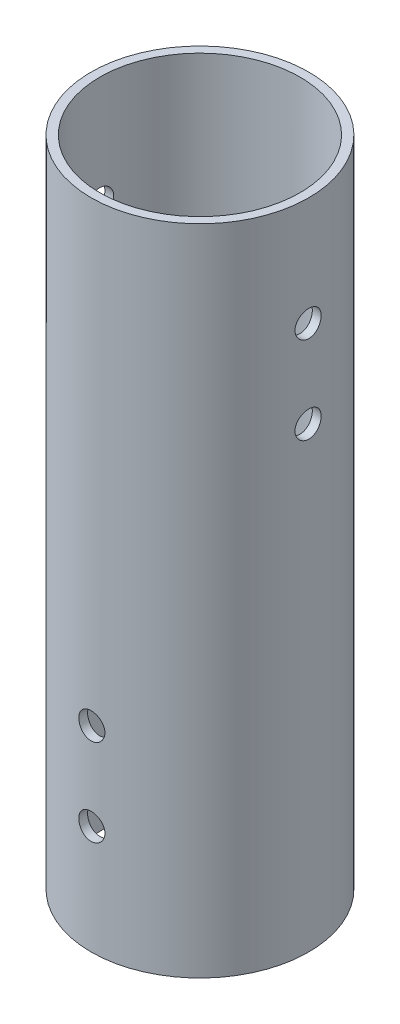
SolidWorks part; units mm, degrees
material "Thornel Mat VMA"
ref_plane "前视基准面" through (0, 0, 0) normal (0, 0, 1) x (1, 0, 0)
ref_plane "上视基准面" through (0, 0, 0) normal (0, 1, 0) x (1, 0, 0)
ref_plane "右视基准面" through (0, 0, 0) normal (1, 0, 0) x (0, 0, -1)
other "Configuration Table"
sketch "草图1" plane through (0, 0, 0) normal (0, 1, 0) x (1, 0, 0)
  circle A0 centre (0, 0) radius 25
  circle A1 centre (0, 0) radius 23
  dimension "D1" = 50
  dimension "D2" = 46
extrude "凸台-拉伸1" add sketch "草图1" along normal blind 150
sketch "草图2" plane through (0, 0, 0) normal (0, 0, 1) x (1, 0, 0)
  line L0 (-25, 150) -> (-25, 0) construction
  line L1 (25, 0) -> (-25, 0) construction
  line L2 (25, 0) -> (25, 70) construction
  line L3 (25, 70) -> (-25, 70) construction
  line L4 (-25, 0) -> (-25, 70) construction
  line L5 (-25, 70) -> (25, 0) construction
  line L6 (25, 70) -> (-25, 0) construction
  line L7 (0, 25) -> (0, 45) construction
  circle A0 centre (0, 45) radius 3
  circle A1 centre (0, 25) radius 3
  point P11 (0, 35)
  dimension "D3" = 6
  dimension "D4" = 6
  dimension "D1" = 70
  dimension "D2" = 20
extrude "切除-拉伸1" cut sketch "草图2" against normal through all and the other way through all
sketch "草图3" plane through (0, 0, 0) normal (1, 0, 0) x (0, 0, -1)
  line L0 (25, 48) -> (25, 150) construction
  line L1 (-25, 150) -> (25, 150) construction
  line L2 (-25, 150) -> (-25, 80) construction
  line L3 (-25, 80) -> (25, 80) construction
  line L4 (25, 150) -> (25, 80) construction
  line L5 (-25, 150) -> (25, 80) construction
  line L6 (25, 150) -> (-25, 80) construction
  line L7 (0, 105) -> (0, 125) construction
  circle A0 centre (0, 125) radius 3
  circle A1 centre (0, 105) radius 3
  point P11 (0, 115)
  dimension "D3" = 6
  dimension "D4" = 6
  dimension "D1" = 70
  dimension "D2" = 20
extrude "切除-拉伸2" cut sketch "草图3" against normal through all and the other way through all
